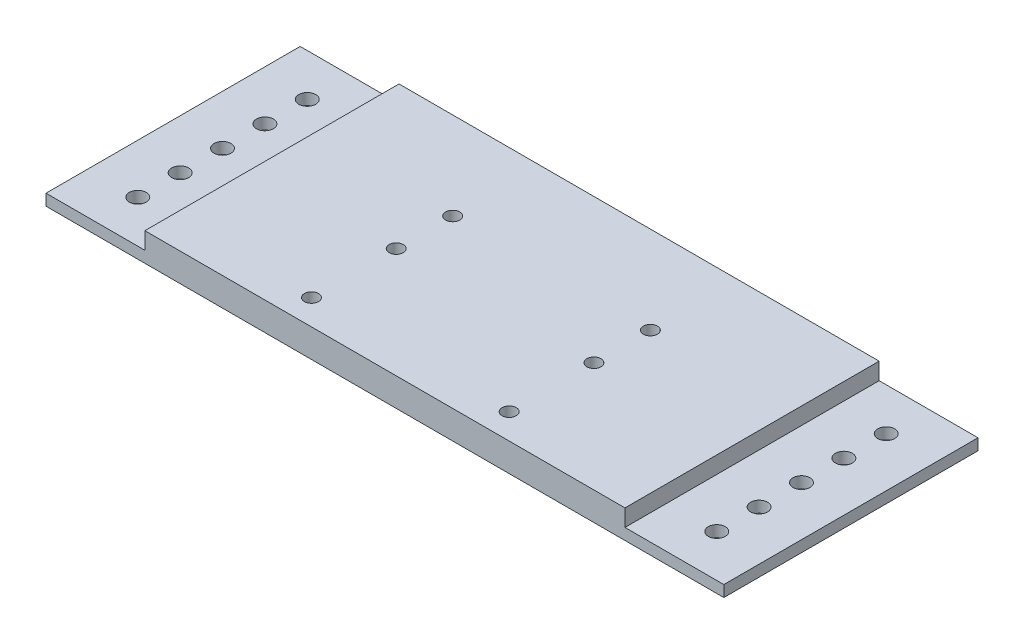
SolidWorks part; units mm, degrees
ref_plane "前视基准面" through (0, 0, 0) normal (0, 0, 1) x (1, 0, 0)
ref_plane "上视基准面" through (0, 0, 0) normal (0, 1, 0) x (1, 0, 0)
ref_plane "右视基准面" through (0, 0, 0) normal (1, 0, 0) x (0, 0, -1)
other "Configuration Table"
sketch "草图1" plane through (0, 0, 0) normal (0, 1, 0) x (1, 0, 0)
  line L1 (0, 0) -> (240, 0)
  line L2 (0, 0) -> (0, -90)
  line L3 (0, -90) -> (240, -90)
  line L4 (240, 0) -> (240, -90)
  dimension "D1" = 240
  dimension "D2" = 90
extrude "凸台-拉伸1" add sketch "草图1" along normal blind 4
sketch "草图2" plane through (0, 4, 0) normal (0, 1, 0) x (1, 0, 0)
  line L0 (0, -90) -> (240, -90) construction
  line L1 (35, 0) -> (205, 0)
  line L2 (35, 0) -> (35, -90)
  line L3 (35, -90) -> (205, -90)
  line L4 (205, 0) -> (205, -90)
  line L5 (35, 0) -> (205, -90) construction
  line L6 (35, -90) -> (205, 0) construction
  line L7 (240, 0) -> (0, 0) construction
  line L8 (240, -90) -> (240, 0) construction
  line L9 (0, 0) -> (0, -90) construction
  point P0 (120, -45)
  dimension "D1" = 170
  dimension "D2" = 35
  dimension "D3" = 35
extrude "凸台-拉伸2" add sketch "草图2" along normal blind 6
sketch "草图3" plane through (0, 4, 0) normal (0, 1, 0) x (1, 0, 0)
  line L0 (120, 0) -> (120, -90) construction
  line L1 (205, 0) -> (35, 0) construction
  line L2 (35, -90) -> (205, -90) construction
  line L3 (17.5, 0) -> (17.5, -90) construction
  line L4 (35, 0) -> (0, 0) construction
  line L5 (0, -90) -> (35, -90) construction
  line L6 (222.5, 0) -> (222.5, -90) construction
  circle A0 centre (17.5, -15) radius 3
  circle A1 centre (17.5, -30) radius 3
  circle A2 centre (17.5, -45) radius 3
  circle A3 centre (17.5, -60) radius 3
  circle A4 centre (17.5, -75) radius 3
  circle A5 centre (222.5, -75) radius 3
  circle A6 centre (222.5, -60) radius 3
  circle A7 centre (222.5, -45) radius 3
  circle A8 centre (222.5, -30) radius 3
  circle A9 centre (222.5, -15) radius 3
  dimension "D1" = 6
  dimension "D2" = 15
  dimension "D3" = 5
extrude "切除-拉伸1" cut sketch "草图3" against normal through all
sketch "草图4" plane through (0, 0, 0) normal (0, -1, 0) x (1, 0, 0)
  line L0 (120, 112.4585) -> (120, -34.2891) construction
  line L7 (85, 90) -> (85, 0) construction
  line L9 (155, 90) -> (155, 0) construction
  circle A0 centre (85, 81) radius 2.5
  circle A1 centre (155, 81) radius 2.5
  circle A2 centre (85, 31) radius 2.5
  circle A3 centre (155, 31) radius 2.5
  circle A4 centre (85, 51) radius 2.5
  circle A5 centre (155, 51) radius 2.5
  dimension "D3" = 5
  dimension "D4" = 5
  dimension "D5" = 5
  dimension "D6" = 5
  dimension "D9" = 50
  dimension "D10" = 50
  dimension "D11" = 5
  dimension "D12" = 5
  dimension "D13" = 20
  dimension "D14" = 20
  dimension "D1" = 35
  dimension "D2" = 35
extrude "切除-拉伸5" cut sketch "草图4" against normal through all
